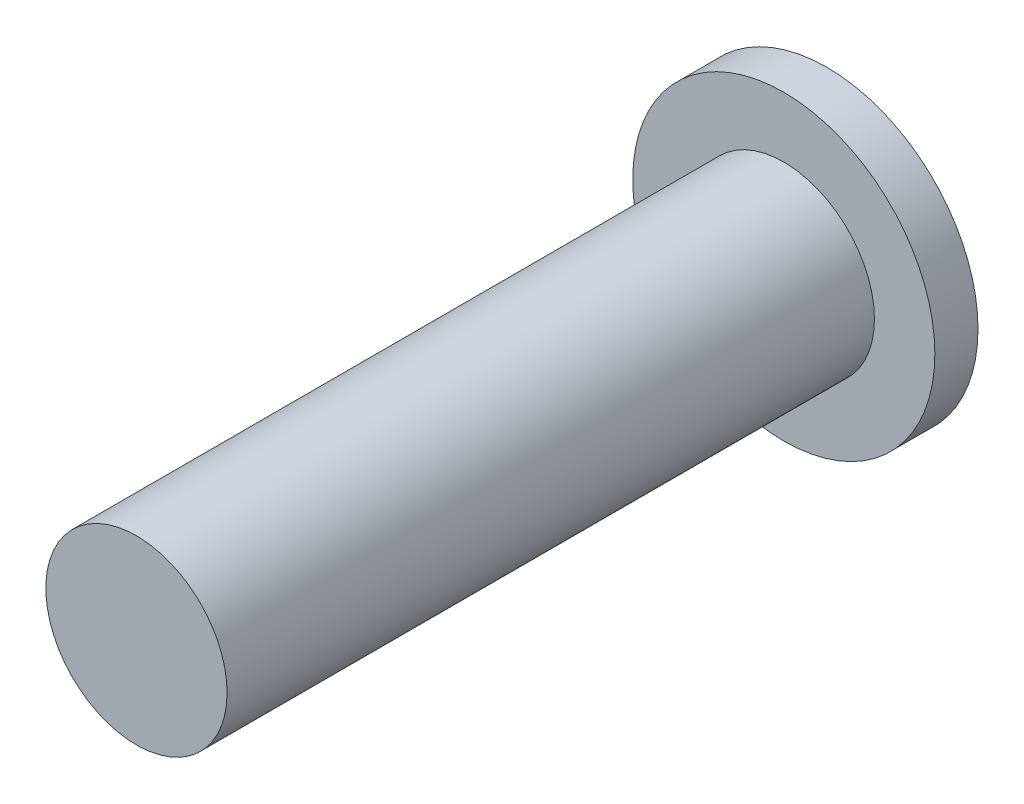
SolidWorks part; units mm, degrees
ref_plane "前视基准面" through (0, 0, 0) normal (0, 0, 1) x (1, 0, 0)
ref_plane "上视基准面" through (0, 0, 0) normal (0, 1, 0) x (1, 0, 0)
ref_plane "右视基准面" through (0, 0, 0) normal (1, 0, 0) x (0, 0, -1)
other "Configuration Table"
sketch "草图1" plane through (0, 0, 0) normal (0, 0, 1) x (1, 0, 0)
  circle A0 centre (0, 0) radius 4.2
  point P5 (0, 0)
  dimension "D1" = 8.4
extrude "凸台-拉伸1" add sketch "草图1" along normal blind 30
sketch "草图3" plane through (0, 0, 0) normal (0, 0, -1) x (-1, 0, 0)
  circle A0 centre (0, 0) radius 7
extrude "凸台-拉伸3" add sketch "草图3" along normal blind 2
